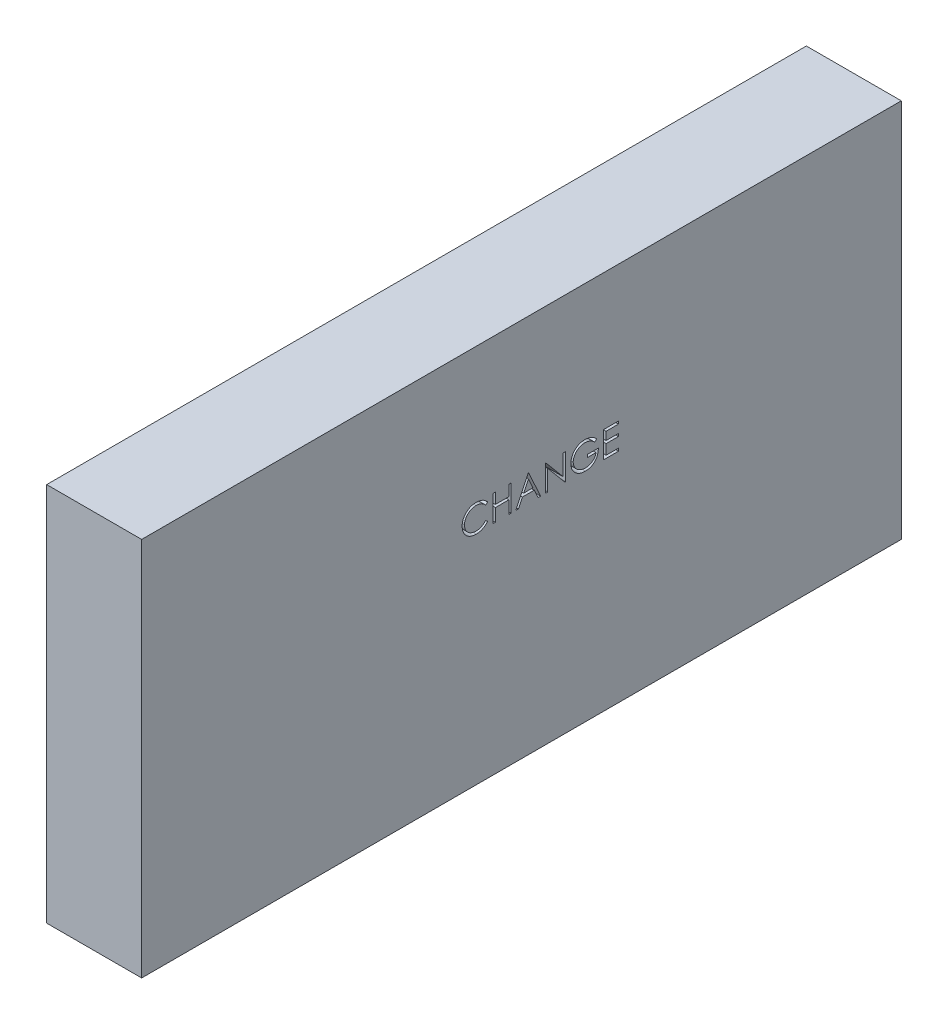
SolidWorks part; units mm, degrees
ref_plane "Front" through (0, 0, 0) normal (0, 0, 1) x (1, 0, 0)
ref_plane "Top" through (0, 0, 0) normal (0, 1, 0) x (1, 0, 0)
ref_plane "Right" through (0, 0, 0) normal (1, 0, 0) x (0, 0, -1)
sketch "Sketch1" plane through (0, 0, 0) normal (0, 0, 1) x (1, 0, 0)
  line L1 (-6.35, 25.4) -> (6.35, 25.4)
  line L2 (-6.35, 25.4) -> (-6.35, -25.4)
  line L3 (-6.35, -25.4) -> (6.35, -25.4)
  line L4 (6.35, 25.4) -> (6.35, -25.4)
  point P4 (0, 25.4)
  point P5 (6.35, 0)
  dimension "D1" = 12.7
  dimension "D2" = 50.8
extrude "Extrude1" add sketch "Sketch1" along normal mid plane 101.6
sketch "Sketch2" plane through (6.35, 0, 0) normal (1, 0, 0) x (0, 0, -1)
  text T0 "CHANGE"
extrude "Cut-Extrude1" cut sketch "Sketch2" against normal through all
